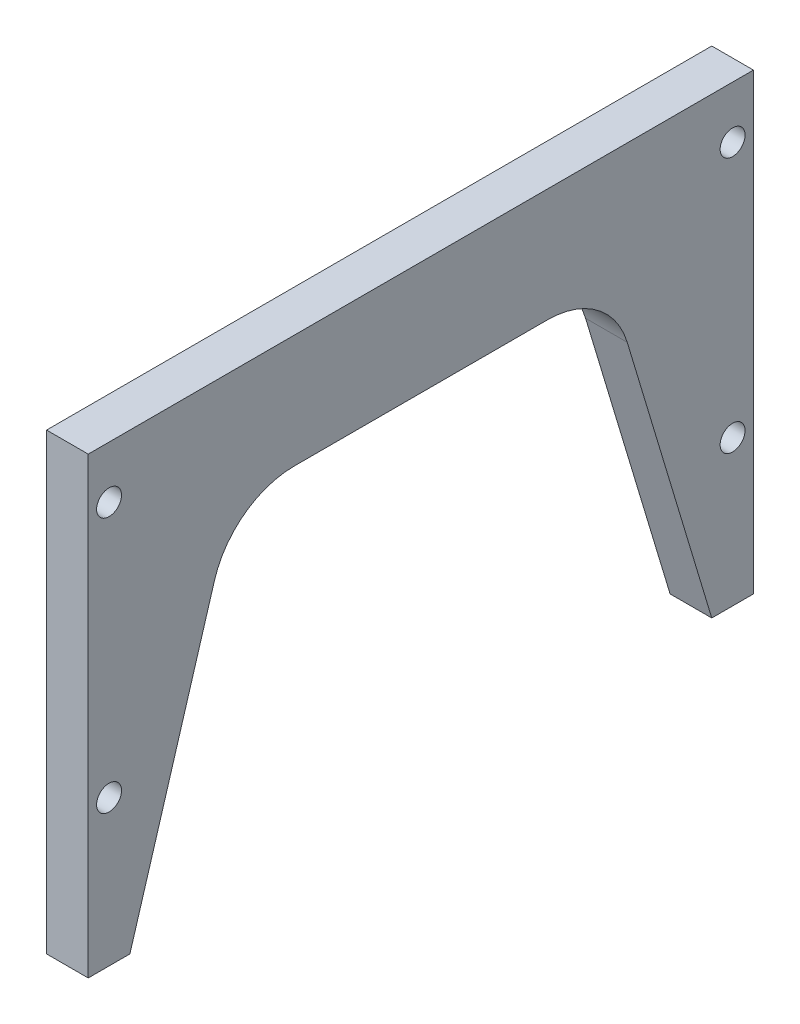
SolidWorks part; units mm, degrees
ref_plane "Front Plane" through (0, 0, 0) normal (0, 0, 1) x (1, 0, 0)
ref_plane "Top Plane" through (0, 0, 0) normal (0, 1, 0) x (1, 0, 0)
ref_plane "Right Plane" through (0, 0, 0) normal (1, 0, 0) x (0, 0, -1)
sketch "Sketch1" plane through (-60.9331, 0, 0) normal (-1, 0, 0) x (0, 0, 1)
  line L0 (0, 53.2785) -> (-6.35, 53.2785) construction
  line L4 (-6.35, 53.2785) -> (-6.35, -15.875) construction
  line L5 (-6.35, -15.875) -> (0, -15.875) construction
  line L6 (0, -15.875) -> (0, 53.2785) construction
  line L8 (-95.0394, -15.875) -> (-95.0394, 53.2785) construction
  line L10 (-101.3894, 53.2785) -> (-101.3894, -15.875) construction
  line L11 (-101.3894, -15.875) -> (-95.0394, -15.875) construction
  line L12 (-95.0394, 46.9285) -> (-6.35, 46.9285)
  line L14 (0, 53.2785) -> (-101.3894, 53.2785)
  line L16 (-6.35, 46.9285) -> (-6.35, -15.875)
  line L17 (-6.35, -15.875) -> (0, -15.875)
  line L18 (0, -15.875) -> (0, 53.2785)
  line L20 (-95.0394, -15.875) -> (-95.0394, 46.9285)
  line L22 (-101.3894, 53.2785) -> (-101.3894, -15.875)
  line L23 (-101.3894, -15.875) -> (-95.0394, -15.875)
  line L24 (-50.6947, 46.9285) -> (-50.6947, -15.875) construction
  line L25 (-95.0394, 46.9285) -> (-79.4346, 36.0018) construction
  line L26 (-95.0394, -15.875) -> (-82.1543, 26.9601)
  line L27 (-69.9927, 36.0018) -> (-31.3967, 36.0018)
  line L28 (-6.35, -15.875) -> (-19.2351, 26.9601)
  arc A0 (-69.9927, 36.0018) -> (-82.1543, 26.9601) centre (-69.9927, 23.3018) ccw
  arc A1 (-31.3967, 36.0018) -> (-19.2351, 26.9601) centre (-31.3967, 23.3018) cw
  point P23 (-50.6947, 36.0018)
  line M7 (-95.0394, -15.875) -> (-95.0394, 53.2785)
  line M8 (-95.0394, 53.2785) -> (-101.3894, 53.2785)
  line M9 (-101.3894, 53.2785) -> (-101.3894, -15.875)
  line M10 (-101.3894, -15.875) -> (-95.0394, -15.875)
  dimension "D3" = 12.7
  dimension "D1" = 35
  dimension "D2" = 19.05
  dimension "D4" = 6.35
extrude "Boss-Extrude1" add sketch "Sketch1" along normal blind 6.35 contours L14 L22 L12 L16 L17 L18 M8 | M10 M7 M8 M9 | L27 A1 L28 L16 L12 L26 A0 M7
hole_wizard "#6 Clearance Hole1" positions "Sketch2" profile "Sketch3" hole size "#6" standard "ANSI Inch"
sketch "Sketch2" plane through (-67.2831, 0, 0) normal (-1, 0, 0) x (0, 0, 1)
  point P0 (-3.175, 45.341)
  point P4 (-3.175, 6.35)
  point P7 (-98.2144, 6.35)
  point P10 (-98.2144, 45.341)
sketch "Sketch3" plane through (-67.2831, 45.341, -3.175) normal (0, 1, 0) x (0, 0, 1)
  line L0 (0, 0) -> (0, 10.5388)
  line L1 (0, 10.5388) -> (1.8986, 9.398)
  line L2 (1.8986, 9.398) -> (1.8986, 0)
  line L5 (1.8986, 0) -> (0, 0)
  line L10 (0, 10.5388) -> (-1.8987, 9.398) construction
  line L11 (0, -6.35) -> (0, 107.95) construction
  dimension "Hole Dia." = 3.7973
  dimension "Hole Depth" = 9.398
  dimension "Drill Angle" = 118
